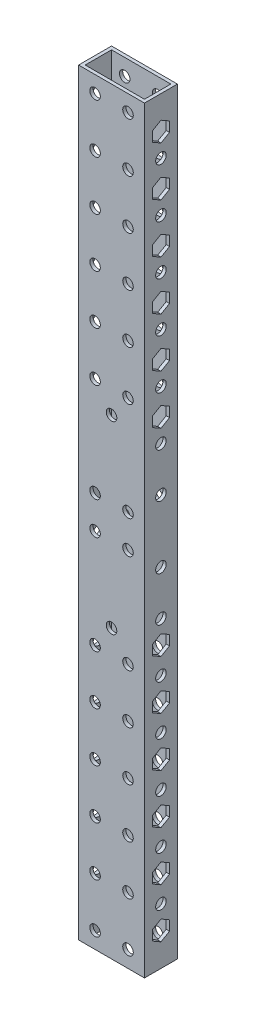
SolidWorks part; units mm, degrees
ref_plane "前视基准面" through (0, 0, 0) normal (0, 0, 1) x (1, 0, 0)
ref_plane "上视基准面" through (0, 0, 0) normal (0, 1, 0) x (1, 0, 0)
ref_plane "右视基准面" through (0, 0, 0) normal (1, 0, 0) x (0, 0, -1)
other "Configuration Table"
sketch "草图1" plane through (0, 0, 0) normal (0, 1, 0) x (1, 0, 0)
  line L1 (-10, -5) -> (10, -5)
  line L2 (-10, -5) -> (-10, 5)
  line L3 (-10, 5) -> (10, 5)
  line L4 (10, -5) -> (10, 5)
  line L5 (-10, -5) -> (10, 5) construction
  line L6 (-10, 5) -> (10, -5) construction
  point P0 (0, 0)
  dimension "D1" = 20
  dimension "D2" = 10
extrude "拉伸-薄壁1" add sketch "草图1" along normal blind 230 thin thin type one direction reverse wall 1
sketch "草图3" plane through (0, 0, 5) normal (0, 0, 1) x (1, 0, 0)
  line L0 (-10, 115) -> (10, 115) construction
  line L1 (-10, 230) -> (-10, 0) construction
  line L2 (10, 230) -> (10, 0) construction
  line L3 (0, 375) -> (0, 380.2879) construction
  line L4 (-10, 230) -> (10, 230) construction
  circle A0 centre (0, 143) radius 1.6
  circle A1 centre (0, 87) radius 1.6
  circle A2 centre (-5, 225) radius 1.6
  circle A3 centre (5, 225) radius 1.6
  circle A4 centre (-5, 210) radius 1.6
  circle A5 centre (5, 210) radius 1.6
  circle A6 centre (-5, 195) radius 1.6
  circle A7 centre (5, 195) radius 1.6
  circle A8 centre (-5, 180) radius 1.6
  circle A9 centre (5, 180) radius 1.6
  circle A10 centre (-5, 165) radius 1.6
  circle A11 centre (5, 165) radius 1.6
  circle A12 centre (-5, 150) radius 1.6
  circle A13 centre (5, 150) radius 1.6
  circle A14 centre (5, 80) radius 1.6
  circle A15 centre (-5, 80) radius 1.6
  circle A16 centre (5, 65) radius 1.6
  circle A17 centre (-5, 65) radius 1.6
  circle A18 centre (5, 50) radius 1.6
  circle A19 centre (-5, 50) radius 1.6
  circle A20 centre (5, 35) radius 1.6
  circle A21 centre (-5, 35) radius 1.6
  circle A22 centre (5, 20) radius 1.6
  circle A23 centre (-5, 20) radius 1.6
  circle A24 centre (5, 5) radius 1.6
  circle A25 centre (-5, 5) radius 1.6
  dimension "D2" = 3.2
  dimension "D3" = 3.2
  dimension "D1" = 28
  dimension "D4" = 5
  dimension "D5" = 5
  dimension "D6" = 15
extrude "切除-拉伸1" cut sketch "草图3" against normal through all
sketch "草图4" plane through (10, 0, 0) normal (1, 0, 0) x (0, 0, -1)
  line L0 (-5, 115) -> (5, 115) construction
  line L1 (-5, 230) -> (-5, 0) construction
  line L2 (5, 230) -> (5, 0) construction
  line L3 (0, 230) -> (0, 115) construction
  line L4 (-5, 230) -> (5, 230) construction
  line L5 (0, 202) -> (2.5981, 203.5)
  line L6 (0, 223) -> (-2.5981, 221.5)
  line L7 (-2.5981, 221.5) -> (-2.5981, 218.5)
  line L8 (-2.5981, 218.5) -> (0, 217)
  line L9 (0, 217) -> (2.5981, 218.5)
  line L10 (2.5981, 218.5) -> (2.5981, 221.5)
  line L11 (2.5981, 221.5) -> (0, 223)
  line L12 (-2.5981, 206.5) -> (-2.5981, 203.5)
  line L13 (-2.5981, 203.5) -> (0, 202)
  line L14 (0, 208) -> (-2.5981, 206.5)
  line L15 (2.5981, 206.5) -> (0, 208)
  line L16 (2.5981, 203.5) -> (2.5981, 206.5)
  line L17 (0, 187) -> (2.5981, 188.5)
  line L18 (-2.5981, 191.5) -> (-2.5981, 188.5)
  line L19 (-2.5981, 188.5) -> (0, 187)
  line L20 (0, 193) -> (-2.5981, 191.5)
  line L21 (2.5981, 191.5) -> (0, 193)
  line L22 (2.5981, 188.5) -> (2.5981, 191.5)
  line L23 (0, 172) -> (2.5981, 173.5)
  line L24 (-2.5981, 176.5) -> (-2.5981, 173.5)
  line L25 (-2.5981, 173.5) -> (0, 172)
  line L26 (0, 178) -> (-2.5981, 176.5)
  line L27 (2.5981, 176.5) -> (0, 178)
  line L28 (2.5981, 173.5) -> (2.5981, 176.5)
  line L29 (0, 157) -> (2.5981, 158.5)
  line L30 (-2.5981, 161.5) -> (-2.5981, 158.5)
  line L31 (-2.5981, 158.5) -> (0, 157)
  line L32 (0, 163) -> (-2.5981, 161.5)
  line L33 (2.5981, 161.5) -> (0, 163)
  line L34 (2.5981, 158.5) -> (2.5981, 161.5)
  line L35 (0, 142) -> (2.5981, 143.5)
  line L36 (-2.5981, 146.5) -> (-2.5981, 143.5)
  line L37 (-2.5981, 143.5) -> (0, 142)
  line L38 (0, 148) -> (-2.5981, 146.5)
  line L39 (2.5981, 146.5) -> (0, 148)
  line L40 (2.5981, 143.5) -> (2.5981, 146.5)
  line L41 (2.5981, 86.5) -> (2.5981, 83.5)
  line L42 (2.5981, 83.5) -> (0, 82)
  line L43 (0, 82) -> (-2.5981, 83.5)
  line L44 (-2.5981, 86.5) -> (0, 88)
  line L45 (-2.5981, 83.5) -> (-2.5981, 86.5)
  line L46 (0, 88) -> (2.5981, 86.5)
  line L47 (2.5981, 71.5) -> (2.5981, 68.5)
  line L48 (2.5981, 68.5) -> (0, 67)
  line L49 (0, 67) -> (-2.5981, 68.5)
  line L50 (-2.5981, 71.5) -> (0, 73)
  line L51 (-2.5981, 68.5) -> (-2.5981, 71.5)
  line L52 (0, 73) -> (2.5981, 71.5)
  line L53 (2.5981, 56.5) -> (2.5981, 53.5)
  line L54 (2.5981, 53.5) -> (0, 52)
  line L55 (0, 52) -> (-2.5981, 53.5)
  line L56 (-2.5981, 56.5) -> (0, 58)
  line L57 (-2.5981, 53.5) -> (-2.5981, 56.5)
  line L58 (0, 58) -> (2.5981, 56.5)
  line L59 (2.5981, 41.5) -> (2.5981, 38.5)
  line L60 (2.5981, 38.5) -> (0, 37)
  line L61 (0, 37) -> (-2.5981, 38.5)
  line L62 (-2.5981, 41.5) -> (0, 43)
  line L63 (-2.5981, 38.5) -> (-2.5981, 41.5)
  line L64 (0, 43) -> (2.5981, 41.5)
  line L65 (2.5981, 26.5) -> (2.5981, 23.5)
  line L66 (2.5981, 23.5) -> (0, 22)
  line L67 (0, 22) -> (-2.5981, 23.5)
  line L68 (-2.5981, 26.5) -> (0, 28)
  line L69 (-2.5981, 23.5) -> (-2.5981, 26.5)
  line L70 (2.5981, 8.5) -> (0, 7)
  line L71 (2.5981, 11.5) -> (2.5981, 8.5)
  line L72 (0, 13) -> (2.5981, 11.5)
  line L73 (-2.5981, 11.5) -> (0, 13)
  line L74 (-2.5981, 8.5) -> (-2.5981, 11.5)
  line L75 (0, 7) -> (-2.5981, 8.5)
  line L76 (0, 28) -> (2.5981, 26.5)
  circle A0 centre (0, 124.5) radius 1.6
  circle A1 centre (0, 105.5) radius 1.6
  circle A2 centre (0, 220) radius 2.5981 construction
  circle A3 centre (0, 213) radius 1.6
  circle A4 centre (0, 198) radius 1.6
  circle A5 centre (0, 205) radius 2.5981 construction
  circle A6 centre (0, 183) radius 1.6
  circle A7 centre (0, 190) radius 2.5981 construction
  circle A8 centre (0, 168) radius 1.6
  circle A9 centre (0, 175) radius 2.5981 construction
  circle A10 centre (0, 153) radius 1.6
  circle A11 centre (0, 160) radius 2.5981 construction
  circle A12 centre (0, 138) radius 1.6
  circle A13 centre (0, 145) radius 2.5981 construction
  circle A14 centre (0, 85) radius 2.5981 construction
  circle A15 centre (0, 70) radius 2.5981 construction
  circle A16 centre (0, 55) radius 2.5981 construction
  circle A17 centre (0, 40) radius 2.5981 construction
  circle A18 centre (0, 25) radius 2.5981 construction
  circle A19 centre (0, 10) radius 2.5981 construction
  circle A20 centre (0, 92) radius 1.6
  circle A21 centre (0, 77) radius 1.6
  circle A22 centre (0, 62) radius 1.6
  circle A23 centre (0, 47) radius 1.6
  circle A24 centre (0, 32) radius 1.6
  circle A25 centre (0, 17) radius 1.6
  dimension "D1" = 3.2
  dimension "D5" = 3.2
  dimension "D2" = 5
  dimension "D3" = 9.5
  dimension "D4" = 3
  dimension "D6" = 10
  dimension "D7" = 7
  dimension "D8" = 15
extrude "切除-拉伸2" cut sketch "草图4" against normal through all
sketch "草图5" plane through (0, 0, -5) normal (0, 0, -1) x (-1, 0, 0)
  line L0 (-10, 115) -> (10, 115) construction
  line L1 (-10, 230) -> (-10, 0) construction
  line L2 (10, 230) -> (10, 0) construction
  line L3 (0, 115) -> (0, 158.9772) construction
  circle A0 centre (-5, 120) radius 1.6
  circle A1 centre (-5, 110) radius 1.6
  circle A2 centre (5, 110) radius 1.6
  circle A3 centre (5, 120) radius 1.6
  dimension "D1" = 3.2
  dimension "D2" = 5
  dimension "D3" = 5
extrude "切除-拉伸3" cut sketch "草图5" against normal through all
